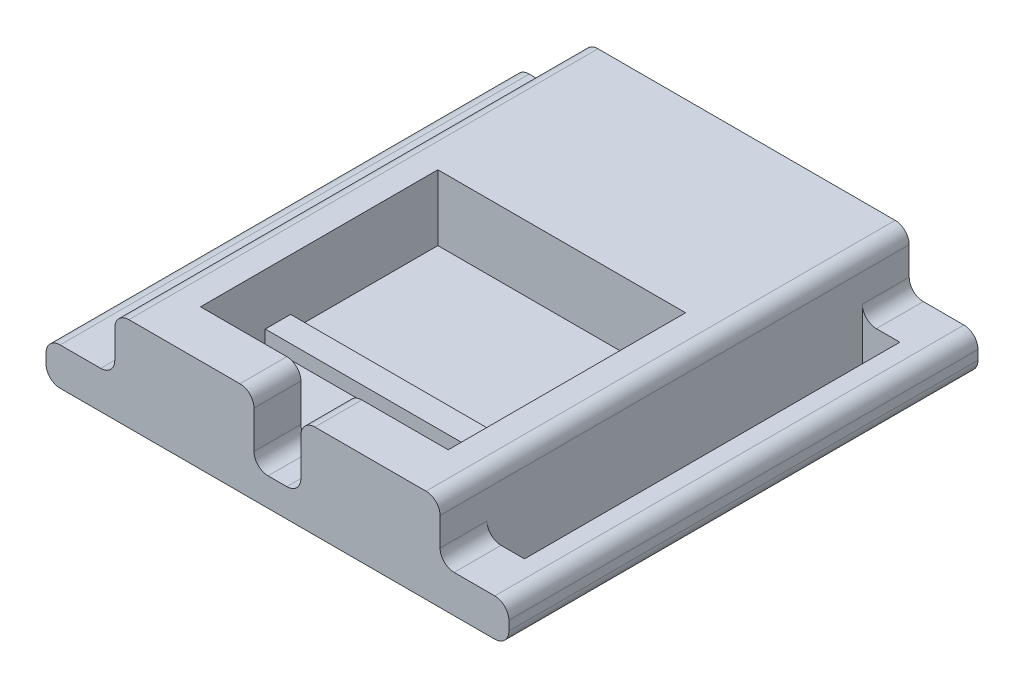
SolidWorks part; units mm, degrees
ref_plane "Front Plane" through (0, 0, 0) normal (0, 0, 1) x (1, 0, 0)
ref_plane "Top Plane" through (0, 0, 0) normal (0, 1, 0) x (1, 0, 0)
ref_plane "Right Plane" through (0, 0, 0) normal (1, 0, 0) x (0, 0, -1)
sketch "Sketch1" plane through (0, 0, 0) normal (0, 1, 0) x (1, 0, 0)
  line L1 (-17.5327, -11.5058) -> (31.7993, -11.5058)
  line L2 (-17.5327, -11.5058) -> (-17.5327, 38.4942)
  line L3 (-17.5327, 38.4942) -> (31.7993, 38.4942)
  line L4 (31.7993, -11.5058) -> (31.7993, 38.4942)
  line L5 (28.4663, -6.5058) -> (24.4663, -6.5058)
  line L6 (28.4663, -6.5058) -> (28.4663, 33.4942)
  line L7 (28.4663, 33.4942) -> (24.4663, 33.4942)
  line L8 (24.4663, -6.5058) -> (24.4663, 33.4942)
  line L9 (-14.1997, 33.4942) -> (-10.1997, 33.4942)
  line L10 (-14.1997, 33.4942) -> (-14.1997, -6.5058)
  line L11 (-14.1997, -6.5058) -> (-10.1997, -6.5058)
  line L12 (-10.1997, 33.4942) -> (-10.1997, -6.5058)
  dimension "D2" = 50
  dimension "D3" = 40
  dimension "D4" = 5
  dimension "D5" = 3.333
  dimension "D6" = 4
  dimension "D7" = 4
  dimension "D8" = 5
  dimension "D9" = 40
  dimension "D10" = 3.333
  dimension "D11" = 34.666
extrude "Boss-Extrude1" add sketch "Sketch1" along normal blind 4
sketch "Sketch2" plane through (0, 4, 0) normal (0, 1, 0) x (1, 0, 0)
  line L6 (-17.5327, -11.5058) -> (31.7993, -11.5058) construction
  line L7 (-10.1997, -11.5058) -> (-6.0657, -11.5058)
  line L8 (-10.1997, -11.5058) -> (-10.1997, 38.4942)
  line L9 (-10.1997, 38.4942) -> (-6.0657, 38.4942)
  line L10 (-6.0657, -11.5058) -> (-6.0657, 38.4942)
  line L11 (31.7993, 38.4942) -> (-17.5327, 38.4942) construction
  line L12 (-10.1997, -6.5058) -> (-10.1997, 33.4942) construction
  dimension "D1" = 4.134
  dimension "D2" = 0
extrude "Boss-Extrude2" add sketch "Sketch2" along normal blind 6
sketch "Sketch8" plane through (0, 4, 0) normal (0, 1, 0) x (1, 0, 0)
  line L0 (31.7993, 38.4942) -> (-6.0657, 38.4942) construction
  line L1 (24.4663, 38.4942) -> (20.3323, 38.4942)
  line L2 (24.4663, 38.4942) -> (24.4663, -11.5058)
  line L3 (24.4663, -11.5058) -> (20.3323, -11.5058)
  line L4 (20.3323, 38.4942) -> (20.3323, -11.5058)
  line L5 (-6.0657, -11.5058) -> (31.7993, -11.5058) construction
  line L6 (24.4663, 33.4942) -> (24.4663, -6.5058) construction
  dimension "D1" = 4.134
  dimension "D2" = 0
extrude "Boss-Extrude6" add sketch "Sketch8" along normal blind 6
sketch "Sketch9" plane through (0, 4, 0) normal (0, 1, 0) x (1, 0, 0)
  line L0 (20.3323, 38.4942) -> (-6.0657, 38.4942) construction
  line L1 (20.3323, 38.4942) -> (-6.0657, 38.4942)
  line L2 (20.3323, 38.4942) -> (20.3323, 18.7942)
  line L3 (20.3323, 18.7942) -> (-6.0657, 18.7942)
  line L4 (-6.0657, 38.4942) -> (-6.0657, 18.7942)
  line L5 (-6.0657, -11.5058) -> (-6.0657, 38.4942) construction
  dimension "D1" = 0
  dimension "D2" = 19.7
extrude "Boss-Extrude7" add sketch "Sketch9" along normal blind 6
sketch "Sketch10" plane through (0, 4, 0) normal (0, 1, 0) x (1, 0, 0)
  line L0 (20.3323, 18.7942) -> (20.3323, -11.5058) construction
  line L1 (-6.0657, -11.5058) -> (20.3323, -11.5058)
  line L2 (-6.0657, -11.5058) -> (-6.0657, -6.5058)
  line L3 (-6.0657, -6.5058) -> (20.3323, -6.5058)
  line L4 (20.3323, -11.5058) -> (20.3323, -6.5058)
  dimension "D1" = 5
extrude "Boss-Extrude8" add sketch "Sketch10" along normal blind 6
sketch "Sketch11" plane through (0, 10, 0) normal (0, 1, 0) x (1, 0, 0)
  line L0 (20.3323, -6.5058) -> (-6.0657, -6.5058) construction
  line L1 (4.6343, -6.5058) -> (9.6343, -6.5058)
  line L2 (4.6343, -6.5058) -> (4.6343, -11.5058)
  line L3 (4.6343, -11.5058) -> (9.6343, -11.5058)
  line L4 (9.6343, -6.5058) -> (9.6343, -11.5058)
  line L5 (-10.1997, -11.5058) -> (24.4663, -11.5058) construction
  line L6 (-10.1997, -6.5058) -> (-10.1997, -11.5058) construction
  dimension "D1" = 5
  dimension "D2" = 14.834
extrude "Cut-Extrude1" cut sketch "Sketch11" against normal blind 7
fillet "Fillet9" radius 1.5 1 edges at (-10.1997, 4, 9.0058)
fillet "Fillet10" radius 1.5 1 edges at (-10.1997, 4, -35.9942)
fillet "Fillet13" radius 1.5 1 edges at (24.4663, 4, -35.9942)
fillet "Fillet14" radius 1.5 1 edges at (24.4663, 4, 9.0058)
fillet "Fillet15" radius 1.5 8 edges at (-17.5327, 0, -13.4942) (-17.5327, 4, -13.4942) (-10.1997, 10, -13.4942) (4.6343, 10, 9.0058) (9.6343, 10, 9.0058) (24.4663, 10, -13.4942) (31.7993, 4, -13.4942) (31.7993, 0, -13.4942)
sketch "Sketch12" plane through (0, 4, 0) normal (0, 1, 0) x (1, 0, 0)
  line L1 (20.3323, 18.7942) -> (-6.0657, 18.7942)
  line L2 (20.3323, 18.7942) -> (20.3323, -6.5058)
  line L3 (20.3323, -6.5058) -> (-6.0657, -6.5058)
  line L4 (-6.0657, 18.7942) -> (-6.0657, -6.5058)
extrude "Cut-Extrude2" cut sketch "Sketch12" against normal blind 1
sketch "Sketch13" plane through (0, 3, 0) normal (0, 1, 0) x (1, 0, 0)
  line L8 (-6.0657, 18.7942) -> (-6.0657, -6.5058) construction
  line L9 (-6.0657, 3.0942) -> (20.3323, 3.0942)
  line L10 (-6.0657, 3.0942) -> (-6.0657, 0.3942)
  line L11 (-6.0657, 0.3942) -> (20.3323, 0.3942)
  line L12 (20.3323, 3.0942) -> (20.3323, 0.3942)
  line L13 (20.3323, 18.7942) -> (20.3323, -6.5058) construction
  line L15 (9.6343, -6.5058) -> (20.3323, -6.5058) construction
  dimension "D1" = 2.7
  dimension "D2" = 0
  dimension "D3" = 6.9
extrude "Boss-Extrude10" add sketch "Sketch13" along normal blind 1.5
fillet "Fillet18" radius 1.5 1 edges at (4.6343, 3, 9.0058)
fillet "Fillet19" radius 1.5 1 edges at (9.6343, 3, 9.0058)
